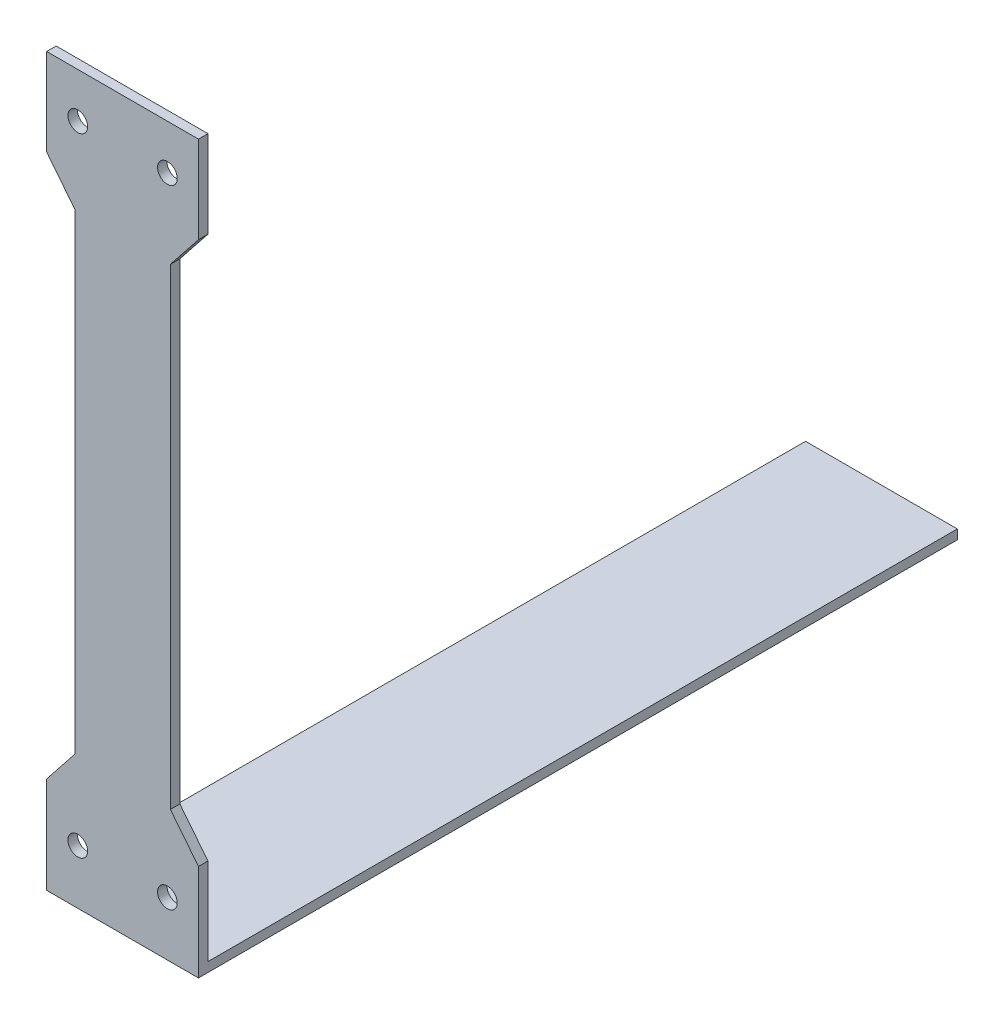
SolidWorks part; units mm, degrees
ref_plane "Front Plane" through (0, 0, 0) normal (0, 0, 1) x (1, 0, 0)
ref_plane "Top Plane" through (0, 0, 0) normal (0, 1, 0) x (1, 0, 0)
ref_plane "Right Plane" through (0, 0, 0) normal (1, 0, 0) x (0, 0, -1)
sketch "Sketch1" plane through (0, 0, 0) normal (0, 0, 1) x (1, 0, 0)
  line L0 (-117, 99.5) -> (-103.5, 116.5) construction
  line L1 (-146.5, 116.5) -> (-133, 99.5) construction
  line L2 (-133, 99.5) -> (-117, 99.5) construction
  line L3 (-117, 99.5) -> (-103.5, 116.5)
  line L4 (-146.5, 116.5) -> (-133, 99.5)
  line L5 (-133, 99.5) -> (-117, 99.5) construction
  line L6 (-250, 120) -> (0, 120) construction
  line L7 (-146.5, 120) -> (-103.5, 120)
  line L8 (0, 0) -> (-250, 0) construction
  line L9 (-103.5, 3.5) -> (-117, 20.5) construction
  line L10 (-117, 20.5) -> (-133, 20.5) construction
  line L11 (-133, 20.5) -> (-146.5, 3.5) construction
  line L12 (-103.5, 0) -> (-146.5, 0)
  line L13 (-103.5, 3.5) -> (-117, 20.5)
  line L14 (-117, 20.5) -> (-133, 20.5) construction
  line L15 (-133, 20.5) -> (-146.5, 3.5)
  line L16 (-103.5, 3.5) -> (-103.5, 0)
  line L17 (-137.7, 14.5815) -> (-137.7, 0)
  line L18 (-146.5, 3.5) -> (-146.5, 0)
  line L19 (-103.5, 116.5) -> (-103.5, 120)
  line L20 (-146.5, 116.5) -> (-146.5, 120)
  line L21 (-117, 20.5) -> (-117, 99.5)
  line L22 (-133, 99.5) -> (-133, 20.5)
  line L23 (-125, 0) -> (-125, 120) construction
  line L24 (-112.3, 14.5815) -> (-112.3, 0)
  line L25 (-137.7, 105.4185) -> (-137.7, 120)
  line L26 (-112.3, 120) -> (-112.3, 105.4185)
  arc A0 (-134.15, 112.5) -> (-130.85, 112.5) centre (-132.5, 112.5) ccw construction
  arc A1 (-130.85, 112.5) -> (-134.15, 112.5) centre (-132.5, 112.5) ccw construction
  arc A2 (-119.15, 112.5) -> (-115.85, 112.5) centre (-117.5, 112.5) ccw construction
  arc A3 (-115.85, 112.5) -> (-119.15, 112.5) centre (-117.5, 112.5) ccw construction
  arc A4 (-134.15, 112.5) -> (-130.85, 112.5) centre (-132.5, 112.5) ccw
  arc A5 (-130.85, 112.5) -> (-134.15, 112.5) centre (-132.5, 112.5) ccw
  arc A6 (-119.15, 112.5) -> (-115.85, 112.5) centre (-117.5, 112.5) ccw
  arc A7 (-115.85, 112.5) -> (-119.15, 112.5) centre (-117.5, 112.5) ccw
  arc A8 (-115.85, 7.5) -> (-119.15, 7.5) centre (-117.5, 7.5) ccw construction
  arc A9 (-119.15, 7.5) -> (-115.85, 7.5) centre (-117.5, 7.5) ccw construction
  arc A10 (-134.15, 7.5) -> (-130.85, 7.5) centre (-132.5, 7.5) ccw construction
  arc A11 (-130.85, 7.5) -> (-134.15, 7.5) centre (-132.5, 7.5) ccw construction
  arc A12 (-115.85, 7.5) -> (-119.15, 7.5) centre (-117.5, 7.5) ccw
  arc A13 (-119.15, 7.5) -> (-115.85, 7.5) centre (-117.5, 7.5) ccw
  arc A14 (-134.15, 7.5) -> (-130.85, 7.5) centre (-132.5, 7.5) ccw
  arc A15 (-130.85, 7.5) -> (-134.15, 7.5) centre (-132.5, 7.5) ccw
  dimension "D1" = 12.7
extrude "Boss-Extrude1" add sketch "Sketch1" along normal blind 1.5875 contours L24 L13 L21 L3 L19 L7 L20 L4 L22 L15 L17 L12 A15 A14 A13 A12 A7 A6 A5 A4
sketch "Sketch2" plane through (0, 0, 0) normal (0, 1, 0) x (1, 0, 0)
  line L0 (-112.3, -1.5875) -> (-112.3, 125.4125)
  line L1 (-112.3, 125.4125) -> (-137.7, 125.4125)
  line L2 (-137.7, 125.4125) -> (-137.7, -1.5875)
  line L3 (-137.7, -1.5875) -> (-112.3, -1.5875) construction
  line L5 (-137.7, -1.5875) -> (-112.3, -1.5875)
  dimension "D1" = 127
extrude "Boss-Extrude2" add sketch "Sketch2" against normal blind 1.5875
